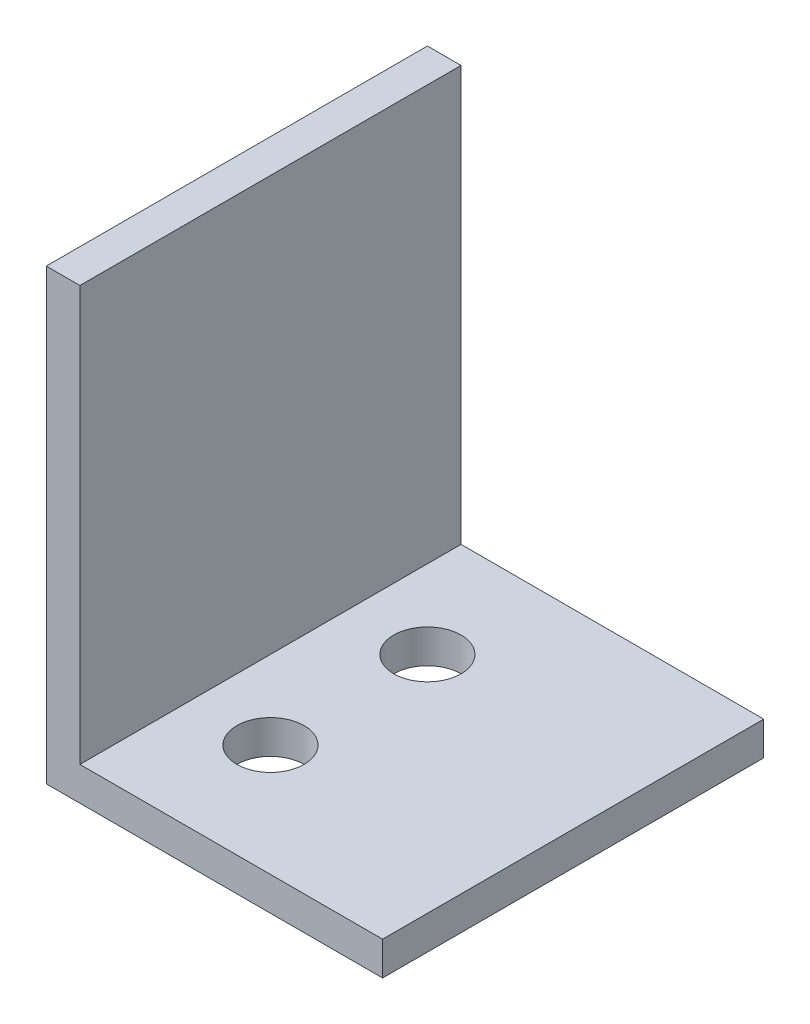
SolidWorks part; units mm, degrees
ref_plane "Plan de face" through (0, 0, 0) normal (0, 0, 1) x (1, 0, 0)
ref_plane "Plan de dessus" through (0, 0, 0) normal (0, 1, 0) x (1, 0, 0)
ref_plane "Plan de droite" through (0, 0, 0) normal (1, 0, 0) x (0, 0, -1)
sketch "Esquisse1" plane through (0, 0, 0) normal (0, 0, 1) x (1, 0, 0)
  line L0 (-23.1133, 4.3188) -> (-23.1133, -15.6812)
  line L1 (-23.1133, -15.6812) -> (-8.1133, -15.6812)
  line L2 (-8.1133, -15.6812) -> (-8.1133, -14.1812)
  line L3 (-8.1133, -14.1812) -> (-21.6133, -14.1812)
  line L4 (-21.6133, -14.1812) -> (-21.6133, 4.3188)
  line L5 (-21.6133, 4.3188) -> (-23.1133, 4.3188)
  dimension "D1" = 20
  dimension "D2" = 1.5
  dimension "D3" = 1.5
  dimension "D4" = 15
extrude "Extrusion1" add sketch "Esquisse1" along normal blind 17
sketch "Esquisse2" plane through (0, -14.1812, 0) normal (0, 1, 0) x (-1, 0, 0)
  line L0 (18.1133, 5) -> (18.1133, 12) construction
  line L2 (21.6133, 17) -> (21.6133, 0) construction
  line L3 (8.1133, 0) -> (21.6133, 0) construction
  circle A0 centre (18.1133, 12) radius 1.5
  circle A1 centre (18.1133, 5) radius 1.5
  dimension "D1" = 7
  dimension "D2" = 3.5
  dimension "D3" = 5
extrude "Extrusion2" cut sketch "Esquisse2" against normal blind 10
